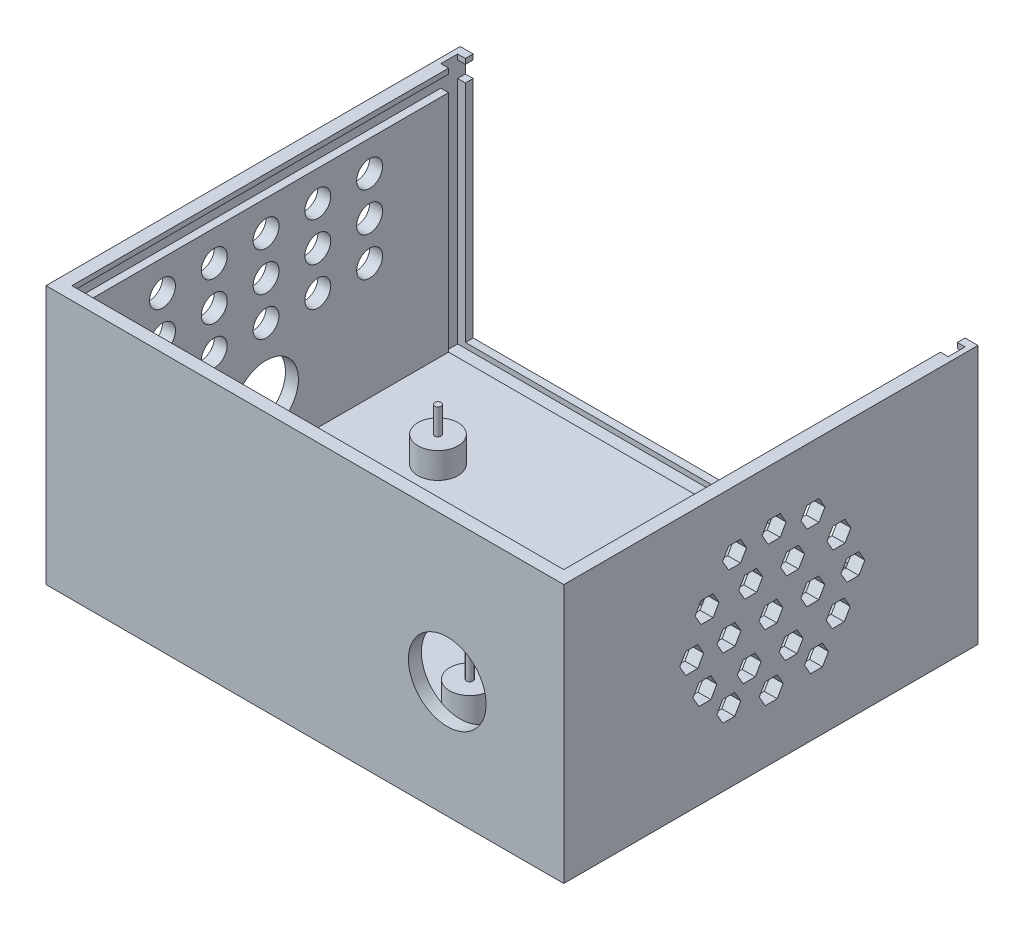
SolidWorks part; units mm, degrees
ref_plane "Front Plane" through (0, 0, 0) normal (0, 0, 1) x (1, 0, 0)
ref_plane "Top Plane" through (0, 0, 0) normal (0, 1, 0) x (1, 0, 0)
ref_plane "Right Plane" through (0, 0, 0) normal (1, 0, 0) x (0, 0, -1)
sketch "Sketch1" plane through (0, 0, 0) normal (0, 1, 0) x (1, 0, 0)
  line L1 (0, 0) -> (200, 0)
  line L2 (0, 0) -> (0, 160)
  line L3 (0, 160) -> (200, 160)
  line L4 (200, 0) -> (200, 160)
  dimension "D1" = 200
  dimension "D2" = 160
extrude "Boss-Extrude1" add sketch "Sketch1" along normal blind 100
shell "Shell2" thickness 5
sketch "Sketch2" plane through (0, 100, 0) normal (0, 1, 0) x (1, 0, 0)
  line L0 (200, 0) -> (200, 160) construction
  line L1 (198, 150.5) -> (2, 150.5)
  line L2 (198, 150.5) -> (198, 157)
  line L3 (198, 157) -> (2, 157)
  line L4 (2, 150.5) -> (2, 157)
  line L5 (0, 160) -> (0, 0) construction
  line L6 (200, 160) -> (195, 160) construction
  dimension "D1" = 2
  dimension "D2" = 2
  dimension "D3" = 3
  dimension "D4" = 6.5
extrude "Cut-Extrude1" cut sketch "Sketch2" against normal offset from surface (97 mm away) 3 up to face at (100, 0, -80)
sketch "Sketch3" plane through (0, 0, -160) normal (0, 0, -1) x (-1, 0, 0)
  line L0 (-200, 100) -> (-200, 0) construction
  line L1 (-198, 98) -> (-2, 98)
  line L2 (-198, 98) -> (-198, 91.8)
  line L3 (-198, 91.8) -> (-2, 91.8)
  line L4 (-2, 98) -> (-2, 91.8)
  line L5 (0, 100) -> (0, 0) construction
  line L6 (-5, 100) -> (-195, 100) construction
  dimension "D1" = 6.2
  dimension "D2" = 2
  dimension "D3" = 2
  dimension "D4" = 2
extrude "Cut-Extrude2" cut sketch "Sketch3" against normal offset from surface (157 mm away) 3 up to face at (100, 50, 0)
sketch "Sketch4" plane through (0, 0, -5) normal (0, 0, -1) x (-1, 0, 0)
  line L0 (-155, 45) -> (-195, 45) construction
  line L2 (-155, 45) -> (-155, 5) construction
  line L3 (-5, 5) -> (-195, 5) construction
  line L4 (-195, 91.8) -> (-195, 5) construction
  circle A0 centre (-155, 45) radius 15
  point P2 (0, 0)
  dimension "D1" = 30
  dimension "D2" = 40
  dimension "D3" = 40
extrude "Cut-Extrude3" cut sketch "Sketch4" against normal through all contours A0
sketch "Sketch5" plane through (200, 0, 0) normal (1, 0, 0) x (0, 0, -1)
  line L0 (0, 50) -> (160, 50) construction
  line L1 (0, 100) -> (0, 0) construction
  line L2 (160, 100) -> (160, 0) construction
  line L3 (68.441, 50.3319) -> (66.1316, 54.3319)
  line L4 (84.6188, 50) -> (82.3094, 54)
  line L5 (82.3094, 54) -> (77.6906, 54)
  line L6 (77.6906, 54) -> (75.3812, 50)
  line L7 (75.3812, 50) -> (77.6906, 46)
  line L8 (77.6906, 46) -> (82.3094, 46)
  line L9 (82.3094, 46) -> (84.6188, 50)
  line L10 (66.1316, 54.3319) -> (61.5128, 54.3319)
  line L11 (61.5128, 54.3319) -> (59.2034, 50.3319)
  line L12 (59.2034, 50.3319) -> (61.5128, 46.3319)
  line L13 (61.5128, 46.3319) -> (66.1316, 46.3319)
  line L14 (66.1316, 46.3319) -> (68.441, 50.3319)
  line L15 (74.5079, 60.1763) -> (76.8173, 64.1763)
  line L16 (76.8173, 64.1763) -> (74.5079, 68.1763)
  line L17 (74.5079, 68.1763) -> (69.8891, 68.1763)
  line L18 (69.8891, 68.1763) -> (67.5797, 64.1763)
  line L19 (67.5797, 64.1763) -> (69.8891, 60.1763)
  line L20 (69.8891, 60.1763) -> (74.5079, 60.1763)
  line L21 (86.0669, 59.8444) -> (90.6857, 59.8444)
  line L22 (90.6857, 59.8444) -> (92.9951, 63.8444)
  line L23 (92.9951, 63.8444) -> (90.6857, 67.8444)
  line L24 (90.6857, 67.8444) -> (86.0669, 67.8444)
  line L25 (86.0669, 67.8444) -> (83.7575, 63.8444)
  line L26 (83.7575, 63.8444) -> (86.0669, 59.8444)
  line L27 (91.559, 49.6681) -> (93.8684, 45.6681)
  line L28 (93.8684, 45.6681) -> (98.4872, 45.6681)
  line L29 (98.4872, 45.6681) -> (100.7966, 49.6681)
  line L30 (100.7966, 49.6681) -> (98.4872, 53.6681)
  line L31 (98.4872, 53.6681) -> (93.8684, 53.6681)
  line L32 (93.8684, 53.6681) -> (91.559, 49.6681)
  line L33 (85.4921, 39.8237) -> (83.1827, 35.8237)
  line L34 (83.1827, 35.8237) -> (85.4921, 31.8237)
  line L35 (85.4921, 31.8237) -> (90.1109, 31.8237)
  line L36 (90.1109, 31.8237) -> (92.4203, 35.8237)
  line L37 (92.4203, 35.8237) -> (90.1109, 39.8237)
  line L38 (90.1109, 39.8237) -> (85.4921, 39.8237)
  line L39 (73.9331, 40.1556) -> (69.3143, 40.1556)
  line L40 (69.3143, 40.1556) -> (67.0049, 36.1556)
  line L41 (67.0049, 36.1556) -> (69.3143, 32.1556)
  line L42 (69.3143, 32.1556) -> (73.9331, 32.1556)
  line L43 (73.9331, 32.1556) -> (76.2425, 36.1556)
  line L44 (76.2425, 36.1556) -> (73.9331, 40.1556)
  line L45 (57.6421, 60.1036) -> (59.9515, 64.1036)
  line L46 (59.9515, 64.1036) -> (57.6421, 68.1036)
  line L47 (57.6421, 68.1036) -> (53.0233, 68.1036)
  line L48 (53.0233, 68.1036) -> (50.7139, 64.1036)
  line L49 (50.7139, 64.1036) -> (53.0233, 60.1036)
  line L50 (53.0233, 60.1036) -> (57.6421, 60.1036)
  line L51 (51.7202, 46.0563) -> (54.0296, 50.0563)
  line L52 (54.0296, 50.0563) -> (51.7202, 54.0563)
  line L53 (51.7202, 54.0563) -> (47.1014, 54.0563)
  line L54 (47.1014, 54.0563) -> (44.792, 50.0563)
  line L55 (44.792, 50.0563) -> (47.1014, 46.0563)
  line L56 (47.1014, 46.0563) -> (51.7202, 46.0563)
  line L57 (56.8158, 33.1108) -> (59.1252, 37.1108)
  line L58 (59.1252, 37.1108) -> (56.8158, 41.1108)
  line L59 (56.8158, 41.1108) -> (52.197, 41.1108)
  line L60 (52.197, 41.1108) -> (49.8876, 37.1108)
  line L61 (49.8876, 37.1108) -> (52.197, 33.1108)
  line L62 (52.197, 33.1108) -> (56.8158, 33.1108)
  line L63 (66.043, 22.9196) -> (68.3524, 26.9196)
  line L64 (68.3524, 26.9196) -> (66.043, 30.9196)
  line L65 (66.043, 30.9196) -> (61.4242, 30.9196)
  line L66 (61.4242, 30.9196) -> (59.1148, 26.9196)
  line L67 (59.1148, 26.9196) -> (61.4242, 22.9196)
  line L68 (61.4242, 22.9196) -> (66.043, 22.9196)
  line L69 (82.4315, 20.5784) -> (84.7409, 24.5784)
  line L70 (84.7409, 24.5784) -> (82.4315, 28.5784)
  line L71 (82.4315, 28.5784) -> (77.8127, 28.5784)
  line L72 (77.8127, 28.5784) -> (75.5033, 24.5784)
  line L73 (75.5033, 24.5784) -> (77.8127, 20.5784)
  line L74 (77.8127, 20.5784) -> (82.4315, 20.5784)
  line L75 (99.9217, 22.5065) -> (102.2311, 26.5065)
  line L76 (102.2311, 26.5065) -> (99.9217, 30.5065)
  line L77 (99.9217, 30.5065) -> (95.3029, 30.5065)
  line L78 (95.3029, 30.5065) -> (92.9935, 26.5065)
  line L79 (92.9935, 26.5065) -> (95.3029, 22.5065)
  line L80 (95.3029, 22.5065) -> (99.9217, 22.5065)
  line L81 (108.3226, 33.3862) -> (110.632, 37.3862)
  line L82 (110.632, 37.3862) -> (108.3226, 41.3862)
  line L83 (108.3226, 41.3862) -> (103.7038, 41.3862)
  line L84 (103.7038, 41.3862) -> (101.3944, 37.3862)
  line L85 (101.3944, 37.3862) -> (103.7038, 33.3862)
  line L86 (103.7038, 33.3862) -> (108.3226, 33.3862)
  line L87 (113.969, 46.0563) -> (116.2784, 50.0563)
  line L88 (116.2784, 50.0563) -> (113.969, 54.0563)
  line L89 (113.969, 54.0563) -> (109.3502, 54.0563)
  line L90 (109.3502, 54.0563) -> (107.0408, 50.0563)
  line L91 (107.0408, 50.0563) -> (109.3502, 46.0563)
  line L92 (109.3502, 46.0563) -> (113.969, 46.0563)
  line L93 (108.598, 59.5528) -> (110.9074, 63.5528)
  line L94 (110.9074, 63.5528) -> (108.598, 67.5528)
  line L95 (108.598, 67.5528) -> (103.9792, 67.5528)
  line L96 (103.9792, 67.5528) -> (101.6698, 63.5528)
  line L97 (101.6698, 63.5528) -> (103.9792, 59.5528)
  line L98 (103.9792, 59.5528) -> (108.598, 59.5528)
  line L99 (98.5747, 71.5281) -> (100.8841, 75.5281)
  line L100 (100.8841, 75.5281) -> (98.5747, 79.5281)
  line L101 (98.5747, 79.5281) -> (93.9559, 79.5281)
  line L102 (93.9559, 79.5281) -> (91.6465, 75.5281)
  line L103 (91.6465, 75.5281) -> (93.9559, 71.5281)
  line L104 (93.9559, 71.5281) -> (98.5747, 71.5281)
  line L105 (83.5633, 74.0009) -> (85.8727, 78.0009)
  line L106 (85.8727, 78.0009) -> (83.5633, 82.0009)
  line L107 (83.5633, 82.0009) -> (78.9445, 82.0009)
  line L108 (78.9445, 82.0009) -> (76.6351, 78.0009)
  line L109 (76.6351, 78.0009) -> (78.9445, 74.0009)
  line L110 (78.9445, 74.0009) -> (83.5633, 74.0009)
  line L111 (68.2766, 73.0307) -> (70.586, 77.0307)
  line L112 (70.586, 77.0307) -> (68.2766, 81.0307)
  line L113 (68.2766, 81.0307) -> (63.6578, 81.0307)
  line L114 (63.6578, 81.0307) -> (61.3484, 77.0307)
  line L115 (61.3484, 77.0307) -> (63.6578, 73.0307)
  line L116 (63.6578, 73.0307) -> (68.2766, 73.0307)
  circle A0 centre (80, 50) radius 4 construction
  circle A1 centre (80, 50) radius 16 construction
  dimension "D1" = 32
  dimension "D2" = 6
extrude "Cut-Extrude4" cut sketch "Sketch5" against normal up to surface (5 mm away) up to face at (195, 48.4, -77.75)
sketch "Sketch6" plane through (0, 5, 0) normal (0, 1, 0) x (1, 0, 0)
  line L0 (195, 77.75) -> (5, 77.75) construction
  line L1 (134.9, 27.8) -> (35, 27.8) construction
  line L2 (134.9, 27.8) -> (134.9, 127.7) construction
  line L3 (134.9, 127.7) -> (35, 127.7) construction
  line L4 (35, 27.8) -> (35, 127.7) construction
  line L5 (195, 5) -> (195, 150.5) construction
  line L6 (5, 150.5) -> (5, 5) construction
  circle A0 centre (128.5, 35.2) radius 1.25
  circle A1 centre (131.4, 118.2) radius 1.25
  circle A2 centre (37.5, 31) radius 1.25
  circle A3 centre (40.4, 111) radius 1.25
  point P18 (134.9, 77.75)
  dimension "D1" = 2.5
  dimension "D2" = 2.5
  dimension "D3" = 2.5
  dimension "D4" = 2.5
  dimension "D5" = 80
  dimension "D6" = 91
  dimension "D7" = 83
  dimension "D8" = 91
  dimension "D9" = 99.9
  dimension "D10" = 99.9
  dimension "D11" = 30
  dimension "D12" = 3.2
  dimension "D13" = 2.5
  dimension "D14" = 3.5
  dimension "D15" = 9.5
extrude "Boss-Extrude2" add sketch "Sketch6" along normal blind 20
sketch "Sketch7" plane through (0, 5, 0) normal (0, 1, 0) x (1, 0, 0)
  circle A0 centre (128.5, 35.2) radius 1.25 construction
  circle A5 centre (131.4, 118.2) radius 1.25 construction
  circle A7 centre (37.5, 31) radius 1.25 construction
  circle A25 centre (131.4, 118.2) radius 1.25
  circle A26 centre (40.4, 111) radius 1.25
  circle A27 centre (40.4, 111) radius 1.25
  circle A28 centre (128.5, 35.2) radius 1.25
  circle A29 centre (37.5, 31) radius 1.25
  circle A30 centre (131.4, 118.2) radius 7.75
  circle A31 centre (40.4, 111) radius 7.75
  circle A32 centre (128.5, 35.2) radius 7.75
  circle A33 centre (37.5, 31) radius 7.75
  dimension "D1" = 0
  dimension "D2" = 6.5
extrude "Boss-Extrude3" add sketch "Sketch7" along normal blind 10
sketch "Sketch8" plane through (0, 0, 0) normal (-1, 0, 0) x (0, 0, 1)
  line L0 (-160, 50) -> (0, 50) construction
  line L1 (-160, 100) -> (-160, 0) construction
  line L2 (0, 100) -> (0, 0) construction
  line L3 (-80, 0) -> (-80, 50) construction
  line L4 (-160, 0) -> (0, 0) construction
  circle A0 centre (-80, 25) radius 12.5
  circle A1 centre (-80, 50) radius 5
  circle A2 centre (-60, 50) radius 5
  circle A3 centre (-40, 50) radius 5
  circle A4 centre (-60, 65) radius 5
  circle A5 centre (-40, 65) radius 5
  circle A6 centre (-60, 80) radius 5
  circle A7 centre (-40, 80) radius 5
  circle A8 centre (-80, 65) radius 5
  circle A9 centre (-80, 80) radius 5
  circle A11 centre (-120, 50) radius 5
  circle A12 centre (-100, 50) radius 5
  circle A13 centre (-120, 65) radius 5
  circle A14 centre (-100, 65) radius 5
  circle A15 centre (-120, 80) radius 5
  circle A16 centre (-100, 80) radius 5
  circle A19 centre (-140, 50) radius 5 [skipped]
  circle A20 centre (-140, 65) radius 5 [skipped]
  circle A21 centre (-140, 80) radius 5 [skipped]
  dimension "D1" = 25
  dimension "D2" = 10
  dimension "D3" = 3
  dimension "D4" = 3
  dimension "D5" = 2
extrude "Cut-Extrude5" cut sketch "Sketch8" against normal up to surface (5 mm away) up to face at (5, 48.4, -77.75)
